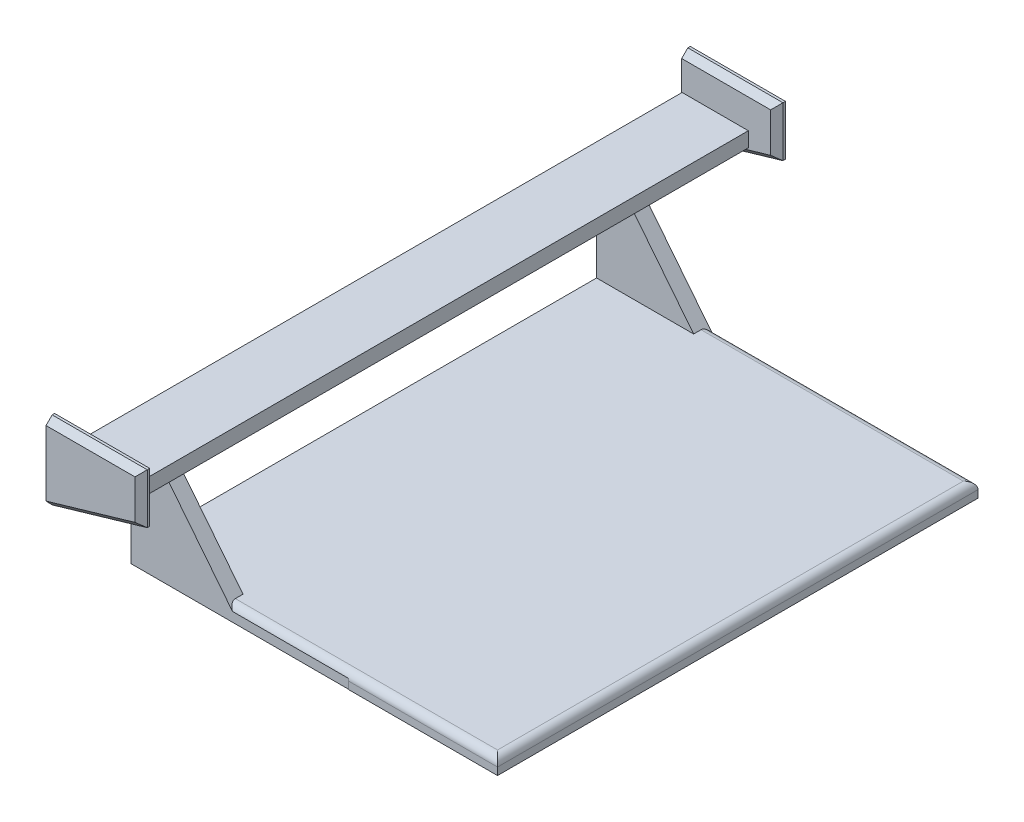
SolidWorks part; units mm, degrees
ref_plane "Front Plane" through (0, 0, 0) normal (0, 0, 1) x (1, 0, 0)
ref_plane "Top Plane" through (0, 0, 0) normal (0, 1, 0) x (1, 0, 0)
ref_plane "Right Plane" through (0, 0, 0) normal (1, 0, 0) x (0, 0, -1)
sketch3d "3DSketch3"
  line L5 (11.684, 0, 25.781) -> (-11.684, 0, 25.781)
  line L6 (11.684, 0, 25.781) -> (11.684, 0, -25.781)
  line L7 (11.684, 0, -25.781) -> (-11.684, 0, -25.781)
  line L8 (-11.684, 0, 25.781) -> (-11.684, 0, -25.781)
  line L9 (11.684, 0, 25.781) -> (-11.684, 0, -25.781) construction
  line L10 (11.684, 0, -25.781) -> (-11.684, 0, 25.781) construction
  point P0 (0, 0, 0)
extrude "Boss-Extrude1" add sketch "3DSketch3" along direction (0, 1, 0) on the side of the normal offset from surface (1.5875 mm away) 1.5875
sketch3d "3DSketch4"
  line L2 (0, 0, 0) -> (-10.08, 12.7, 0)
  line L3 (-11.684, 0, 0) -> (-11.684, 12.7, 0)
  line L4 (-11.684, 12.7, 0) -> (-10.08, 12.7, 0)
  point P1 (0, 0, 0)
  point P5 (0, 12.7, 0)
sketch "Sketch1" plane through (0, 0, 25.781) normal (0, 0, 1) x (1, 0, 0)
  line L0 (0, 0) -> (-10.08, 12.7)
  line L1 (11.684, 0) -> (-11.684, 0) construction
  line L2 (-10.08, 12.7) -> (-11.684, 12.7)
  line L3 (-11.684, 12.7) -> (-11.684, 0)
  line L4 (-11.684, 0) -> (0, 0)
extrude "Boss-Extrude3" add sketch "Sketch1" against normal blind 1.5875 contours L4 L0 L2 L3
mirror "Mirror2" about plane through (0, 0, 0) normal (0, 0, 1) of "Boss-Extrude3"
sketch "Sketch7" plane through (0, 1.5875, 0) normal (0, 1, 0) x (1, 0, 0)
  point P4 (0, 0)
sketch "Sketch9" plane through (0, 12.7, 0) normal (0, 1, 0) x (1, 0, 0)
  line L0 (0, 0) -> (-10.08, 0) construction
  line L1 (-4.5261, -33.3351) -> (-11.6415, -33.3351)
  line L2 (-4.5261, -33.3351) -> (-4.5261, 33.3351)
  line L3 (-4.5261, 33.3351) -> (-11.6415, 33.3351)
  line L4 (-11.6415, -33.3351) -> (-11.6415, 33.3351)
  line L5 (-4.5261, -33.3351) -> (-11.6415, 33.3351) construction
  line L6 (-4.5261, 33.3351) -> (-11.6415, -33.3351) construction
  point P0 (-8.0838, 0)
extrude "Boss-Extrude4" add sketch "Sketch9" along normal blind 1.5875
sketch "Sketch10" plane through (0, 0, 33.3351) normal (0, 0, 1) x (1, 0, 0)
  line L0 (-11.684, 9.7105) -> (-11.684, 18.0856)
  line L1 (-11.684, 0) -> (-11.684, 12.7) construction
  line L2 (-11.684, 18.0856) -> (-1.4701, 18.0856)
  line L3 (-1.4701, 18.0856) -> (-1.4701, 12.7)
  line L4 (-1.4701, 12.7) -> (-11.684, 9.7105)
extrude "Boss-Extrude5" add sketch "Sketch10" along normal blind 1.5875 contours L4 L0 L2 L3
chamfer "Chamfer1" distance 0.6615 angle 45 6 edges at (-6.5771, 11.2053, 33.3351) (-6.5771, 18.0856, 33.3351) (-1.4701, 15.3928, 33.3351) (-6.5771, 11.2053, 34.9226) (-1.4701, 15.3928, 34.9226) (-6.5771, 18.0856, 34.9226)
mirror "Mirror4" about plane through (0, 0, 0) normal (0, 0, 1) of "Boss-Extrude5"
chamfer "Chamfer2" distance 0.6615 angle 45 6 edges at (-6.5771, 11.2053, -33.3351) (-6.5771, 18.0856, -33.3351) (-1.4701, 15.3928, -33.3351) (-6.5771, 11.2053, -34.9226) (-6.5771, 18.0856, -34.9226) (-1.4701, 15.3928, -34.9226)
sketch "Sketch12" plane through (0, 0, 0) normal (0, 1, 0) x (1, 0, 0)
  line L0 (-11.684, -25.781) -> (-11.6415, -24.2581) construction
  line L1 (11.684, 25.781) -> (27.686, 25.781)
  line L2 (11.684, 25.781) -> (11.684, -25.8102)
  line L3 (11.684, -25.8102) -> (27.686, -25.8102)
  line L4 (27.686, 25.781) -> (27.686, -25.8102)
  line L5 (-11.6415, 33.3351) -> (-11.6415, -33.3351) construction
extrude "Boss-Extrude6" add sketch "Sketch12" along normal blind 1.5875 contours L2 L1 L4 L3
fillet "Fillet5" radius 0.7937 3 edges at (19.685, 1.5875, 25.8102) (13.213, 1.5875, -25.781) (27.686, 1.5875, 0.0146)
